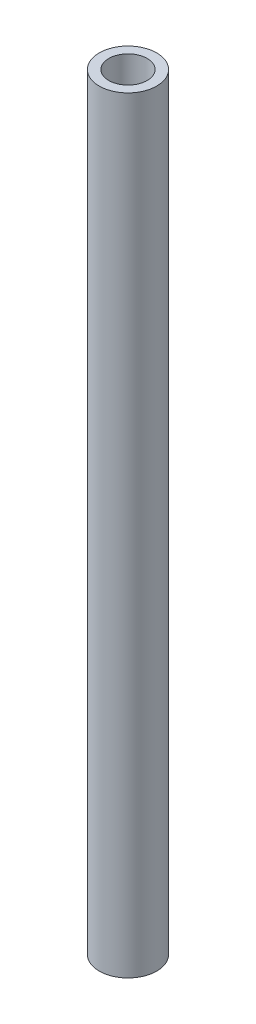
SolidWorks part; units mm, degrees
ref_plane "Front Plane" through (0, 0, 0) normal (0, 0, 1) x (1, 0, 0)
ref_plane "Top Plane" through (0, 0, 0) normal (0, 1, 0) x (1, 0, 0)
ref_plane "Right Plane" through (0, 0, 0) normal (1, 0, 0) x (0, 0, -1)
sketch "Sketch1" plane through (0, 0, 0) normal (0, 1, 0) x (1, 0, 0)
  circle A0 centre (0, 0) radius 2.54
  circle A1 centre (0, 0) radius 3.81
  dimension "D1" = 5.08
  dimension "D2" = 7.62
extrude "Boss-Extrude1" add sketch "Sketch1" along normal blind 101.6
